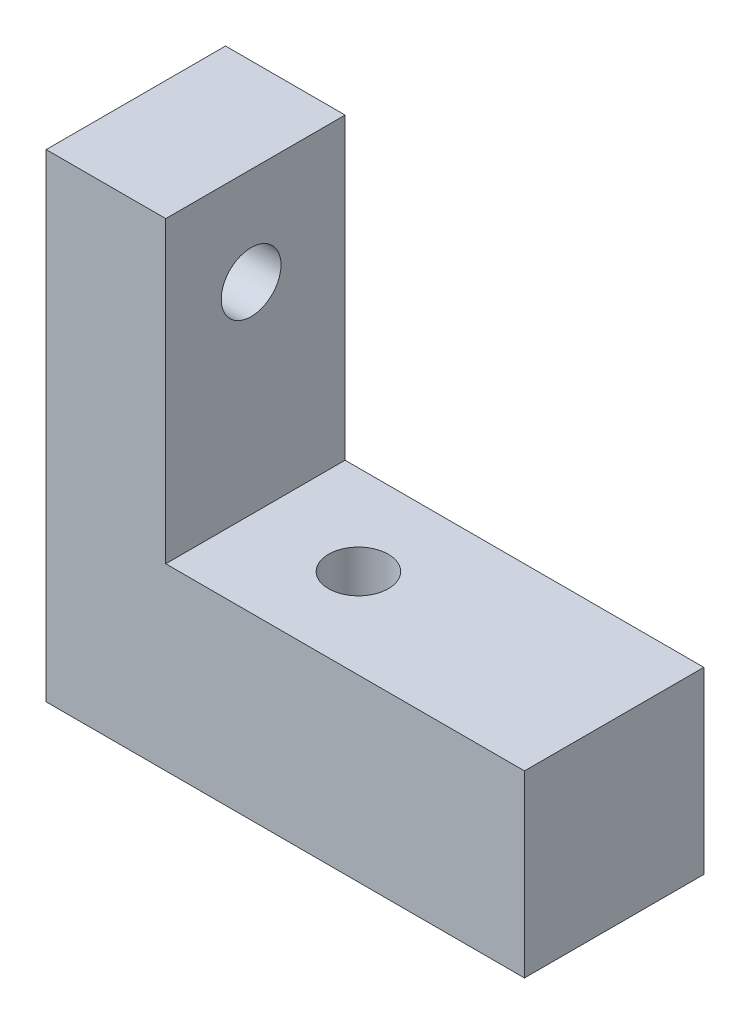
SolidWorks part; units mm, degrees
ref_plane "Front Plane" through (0, 0, 0) normal (0, 0, 1) x (1, 0, 0)
ref_plane "Top Plane" through (0, 0, 0) normal (0, 1, 0) x (1, 0, 0)
ref_plane "Right Plane" through (0, 0, 0) normal (1, 0, 0) x (0, 0, -1)
sketch "Sketch1" plane through (0, 0, 0) normal (0, 0, 1) x (1, 0, 0)
  line L1 (0, 0) -> (80, 0)
  line L2 (0, 0) -> (0, 30)
  line L3 (20, 30) -> (80, 30)
  line L4 (80, 0) -> (80, 30)
  line L6 (0, 30) -> (0, 80)
  line L7 (0, 80) -> (20, 80)
  line L8 (20, 30) -> (20, 80)
  dimension "D1" = 80
  dimension "D2" = 30
  dimension "D3" = 50
  dimension "D4" = 20
extrude "Boss-Extrude1" add sketch "Sketch1" along normal blind 30
sketch "Sketch2" plane through (0, 30, 0) normal (0, 1, 0) x (1, 0, 0)
  circle A0 centre (37.2284, -15) radius 5
  dimension "D1" = 10
extrude "Cut-Extrude1" cut sketch "Sketch2" against normal blind 30
sketch "Sketch3" plane through (20, 0, 0) normal (1, 0, 0) x (0, 0, -1)
  circle A0 centre (-15.7226, 63.664) radius 5
  dimension "D1" = 10
extrude "Cut-Extrude2" cut sketch "Sketch3" against normal blind 30
